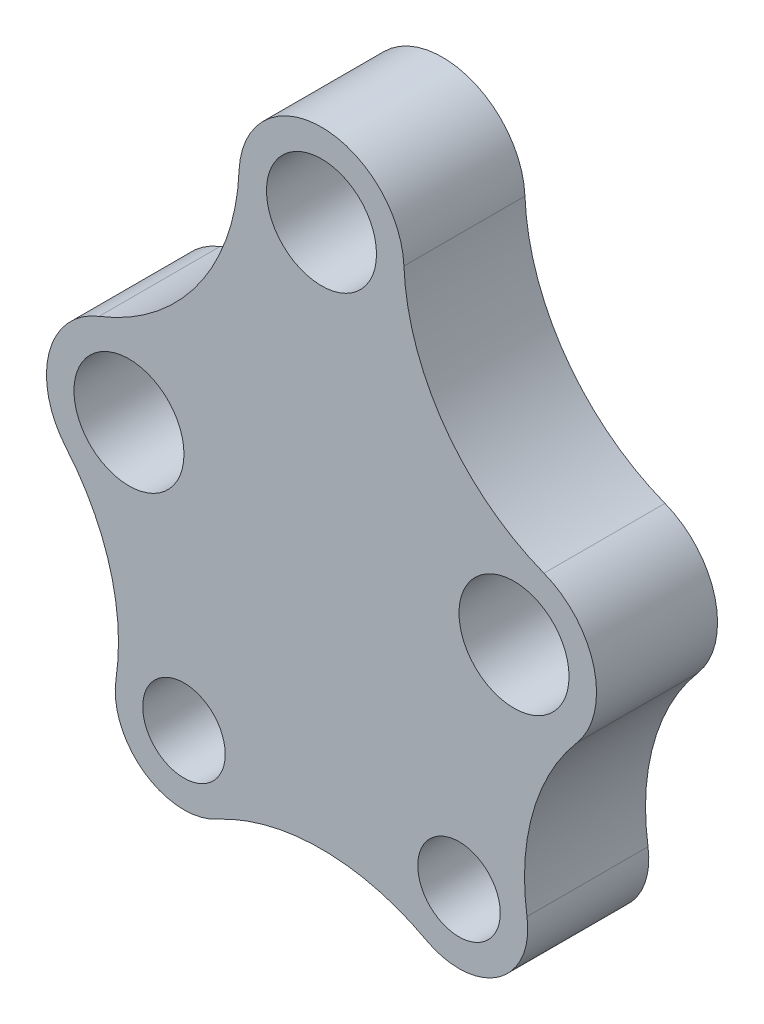
SolidWorks part; units mm, degrees
ref_plane "Front Plane" through (0, 0, 0) normal (0, 0, 1) x (1, 0, 0)
ref_plane "Top Plane" through (0, 0, 0) normal (0, 1, 0) x (1, 0, 0)
ref_plane "Right Plane" through (0, 0, 0) normal (1, 0, 0) x (0, 0, -1)
sketch "Sketch1" plane through (0, 0, 0) normal (0, 0, 1) x (1, 0, 0)
  line L0 (0, 116.1644) -> (0, -95.3425) construction
  circle A0 centre (0, 98) radius 20
  circle A1 centre (0, 98) radius 30
  circle A2 centre (-70, 0) radius 20
  circle A3 centre (-70, 0) radius 30
  circle A4 centre (-50, -87) radius 15
  circle A5 centre (-50, -87) radius 25
  arc A6 (-92.8576, -19.4302) -> (-74.7169, -83.2486) centre (-153.8111, -71.2439) cw
  arc A7 (-29.9748, 99.2288) -> (-80.8839, 27.956) centre (-109.9077, 102.5055) cw
  arc A8 (92.8576, -19.4302) -> (74.7169, -83.2486) centre (153.8111, -71.2439) ccw
  circle A9 centre (50, -87) radius 15
  circle A10 centre (50, -87) radius 25
  circle A11 centre (70, 0) radius 20
  circle A12 centre (70, 0) radius 30
  arc A13 (29.9748, 99.2288) -> (80.8839, 27.956) centre (109.9077, 102.5055) ccw
  arc A14 (-38.0952, -108.9836) -> (38.0952, -108.9836) centre (0, -179.3309) cw
  point P15 (0, 0)
  point P16 (0, 0)
  point P20 (0, 0)
  point P36 (0, 0)
  point P37 (44.2572, -111.3315)
  dimension "D1" = 40
  dimension "D2" = 60
  dimension "D3" = 40
  dimension "D4" = 60
  dimension "D7" = 30
  dimension "D8" = 50
  dimension "D11" = 80
  dimension "D12" = 80
  dimension "D13" = 80
  dimension "D5" = 70
  dimension "D6" = 98
  dimension "D9" = 50
  dimension "D10" = 87
extrude "Boss-Extrude1" add sketch "Sketch1" along normal mid plane 44
